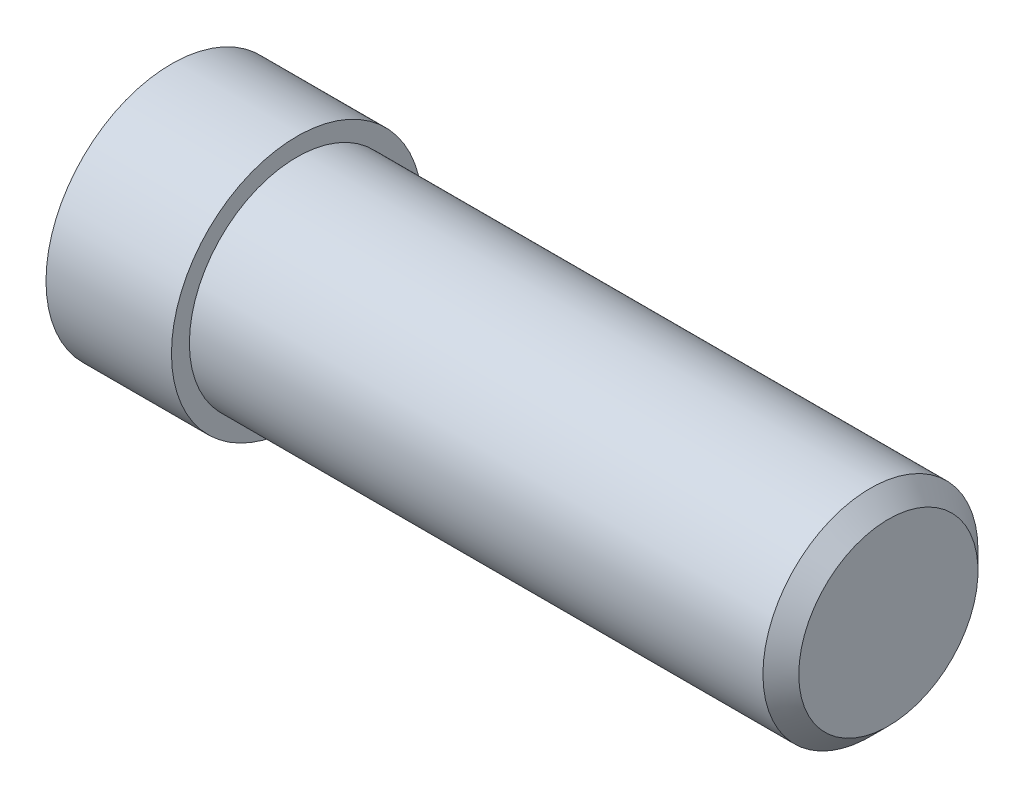
SolidWorks part; units mm, degrees
material "2024-T361"
ref_plane "Front Plane" through (0, 0, 0) normal (0, 0, 1) x (1, 0, 0)
ref_plane "Top Plane" through (0, 0, 0) normal (0, 1, 0) x (1, 0, 0)
ref_plane "Right Plane" through (0, 0, 0) normal (1, 0, 0) x (0, 0, -1)
sketch "Sketch1" plane through (0, 0, 0) normal (0, 0, 1) x (1, 0, 0)
  line L0 (-33.8049, 0) -> (29.8439, 0) construction
  line L1 (-20, 0) -> (-20, 7)
  line L2 (-20, 7) -> (-13, 7)
  line L3 (-13, 7) -> (-13, 6)
  line L4 (-13, 6) -> (20, 6)
  line L5 (20, 6) -> (20, 0)
  line L6 (20, 0) -> (-20, 0)
  point P9 (0, 0)
  dimension "D1" = 7
  dimension "D2" = 7
  dimension "D3" = 33
  dimension "D4" = 6
revolve "Revolve1" add sketch "Sketch1" angle 360 about L0
chamfer "Chamfer1" distance 1 angle 45 1 edges at (20, 0, 6)
